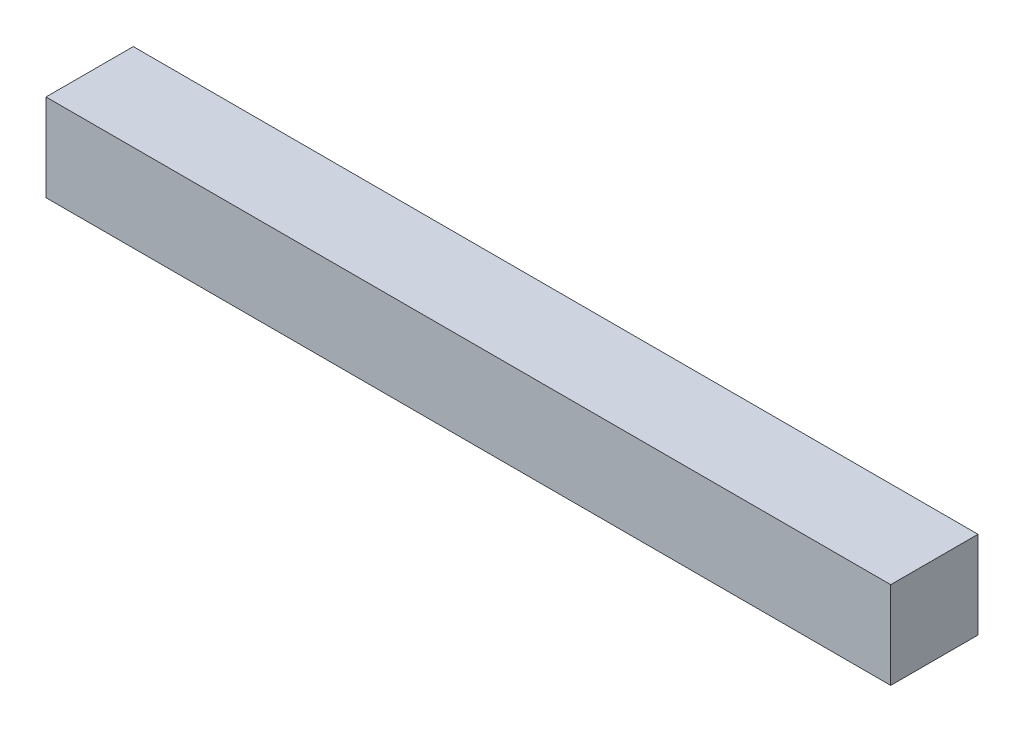
SolidWorks part; units mm, degrees
ref_plane "Front Plane" through (0, 0, 0) normal (0, 0, 1) x (1, 0, 0)
ref_plane "Top Plane" through (0, 0, 0) normal (0, 1, 0) x (1, 0, 0)
ref_plane "Right Plane" through (0, 0, 0) normal (1, 0, 0) x (0, 0, -1)
sketch "Sketch1" plane through (0, 0, 0) normal (0, 0, 1) x (1, 0, 0)
  line L1 (0, 0) -> (96.79, 0)
  line L2 (0, 0) -> (0, -10)
  line L3 (0, -10) -> (96.79, -10)
  line L4 (96.79, 0) -> (96.79, -10)
  line L5 (0, 0) -> (96.79, -10) construction
  line L6 (0, -10) -> (96.79, 0) construction
  point P4 (48.395, -5)
  dimension "D1" = 10
  dimension "D2" = 96.79
extrude "Boss-Extrude1" add sketch "Sketch1" along normal blind 10
